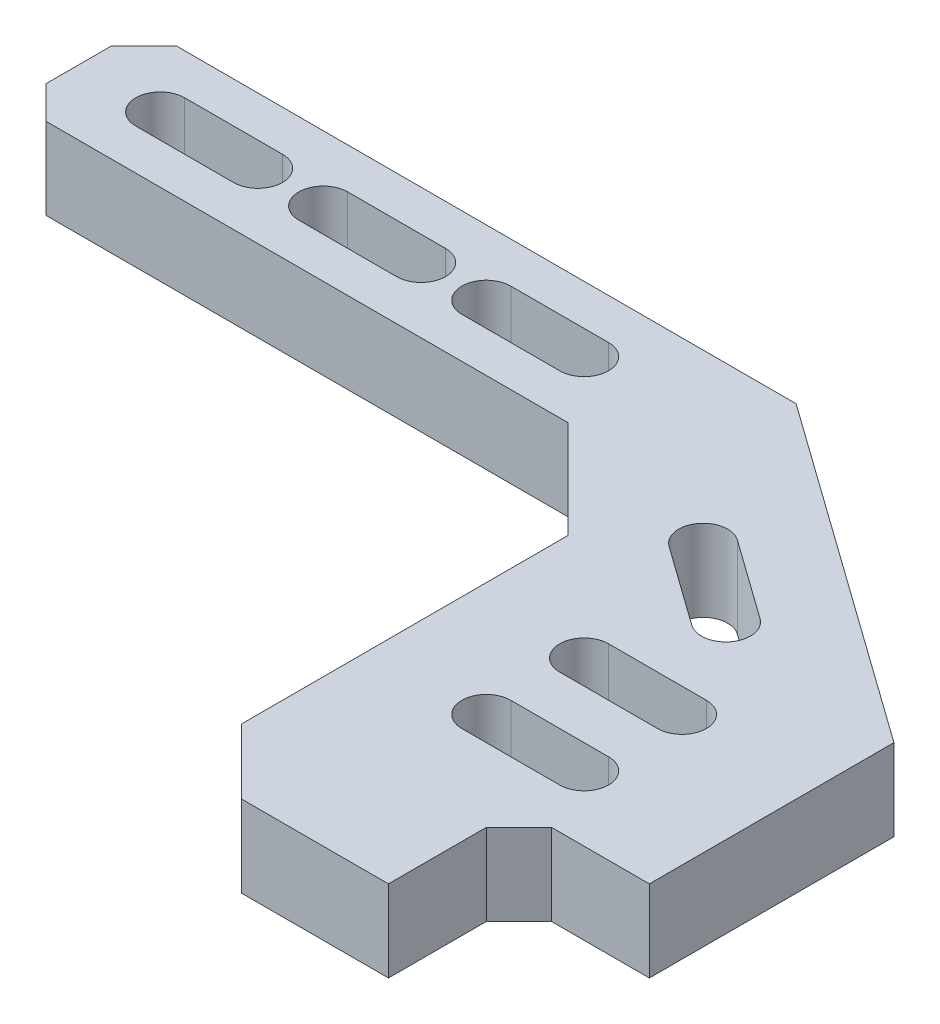
SolidWorks part; units mm, degrees
ref_plane "前视基准面" through (0, 0, 0) normal (0, 0, 1) x (1, 0, 0)
ref_plane "上视基准面" through (0, 0, 0) normal (0, 1, 0) x (1, 0, 0)
ref_plane "右视基准面" through (0, 0, 0) normal (1, 0, 0) x (0, 0, -1)
sketch "草图1" plane through (0, 0, 0) normal (0, 1, 0) x (1, 0, 0)
  line L0 (20, 4) -> (41, -11)
  line L1 (-20, 4) -> (20, 4)
  line L2 (-20, 4) -> (-20, -4)
  line L3 (-20, -4) -> (20, -4)
  line L5 (-20, 4) -> (20, -4) construction
  line L6 (-20, -4) -> (20, 4) construction
  line L8 (20, -4) -> (20, -34)
  line L9 (20, -34) -> (41, -34)
  line L10 (41, -11) -> (41, -34)
  point P0 (0, 0)
  point P5 (0, 0)
  point P8 (41, -6.2971)
  dimension "D1" = 8
  dimension "D2" = 40
  dimension "D3" = 61
  dimension "D4" = 30
  dimension "D5" = 21
  dimension "D6" = 15
extrude "凸台-拉伸1" add sketch "草图1" along normal blind 5
chamfer "倒角1" distance 6 angle 45 1 edges at (20, 2.5, 4)
sketch "草图3" plane through (0, 5, 0) normal (0, 1, 0) x (1, 0, 0)
  line L0 (-15, 0) -> (-9, 0) construction
  line L1 (-15, 1.5) -> (-9, 1.5)
  line L2 (-15, -1.5) -> (-9, -1.5)
  line L3 (-20, 4) -> (-20, -4) construction
  line L4 (-5, -1.5) -> (1, -1.5)
  line L5 (-5, 1.5) -> (1, 1.5)
  line L6 (-5, 0) -> (1, 0) construction
  line L7 (5, -1.5) -> (11, -1.5)
  line L8 (5, 1.5) -> (11, 1.5)
  line L9 (5, 0) -> (11, 0) construction
  line L10 (29.4412, -9.7437) -> (24.5588, -6.2563) construction
  line L11 (28.5693, -10.9643) -> (23.6869, -7.4769)
  line L12 (30.3131, -8.5231) -> (25.4307, -5.0357)
  line L13 (20, 4) -> (-20, 4) construction
  line L14 (20, -10) -> (20, -34) construction
  line L15 (41, -11) -> (20, 4) construction
  line L16 (27, -16) -> (33, -16) construction
  line L17 (27, -14.5) -> (33, -14.5)
  line L18 (27, -17.5) -> (33, -17.5)
  line L20 (33, -34) -> (33, -26)
  line L21 (20, -34) -> (41, -34) construction
  line L22 (33, -26) -> (41, -26)
  line L23 (41, -34) -> (41, -11) construction
  line L24 (33, -34) -> (41, -34)
  line L25 (41, -34) -> (41, -26)
  line L26 (27, -22) -> (33, -22) construction
  line L27 (27, -20.5) -> (33, -20.5)
  line L28 (27, -23.5) -> (33, -23.5)
  arc A0 (-15, 1.5) -> (-15, -1.5) centre (-15, 0) ccw
  arc A1 (-9, -1.5) -> (-9, 1.5) centre (-9, 0) ccw
  arc A2 (-5, 1.5) -> (-5, -1.5) centre (-5, 0) ccw
  arc A3 (1, -1.5) -> (1, 1.5) centre (1, 0) ccw
  arc A4 (5, 1.5) -> (5, -1.5) centre (5, 0) ccw
  arc A5 (11, -1.5) -> (11, 1.5) centre (11, 0) ccw
  arc A6 (28.5693, -10.9643) -> (30.3131, -8.5231) centre (29.4412, -9.7437) ccw
  arc A7 (25.4307, -5.0357) -> (23.6869, -7.4769) centre (24.5588, -6.2563) ccw
  arc A8 (27, -14.5) -> (27, -17.5) centre (27, -16) ccw
  arc A9 (33, -17.5) -> (33, -14.5) centre (33, -16) ccw
  arc A10 (27, -20.5) -> (27, -23.5) centre (27, -22) ccw
  arc A11 (33, -23.5) -> (33, -20.5) centre (33, -22) ccw
  point P2 (-12, 0)
  point P13 (-2, 0)
  point P20 (8, 0)
  point P26 (27, -8)
  point P39 (30, -16)
  point P56 (30, -22)
  dimension "D1" = 6
  dimension "D2" = 5
  dimension "D3" = 3
  dimension "D5" = 4
  dimension "D6" = 12
  dimension "D7" = 7
  dimension "D8" = 10
  dimension "D9" = 10
  dimension "D10" = 8
  dimension "D11" = 13
  dimension "D12" = 2
  dimension "D13" = 4
  dimension "D4" = 3
extrude "切除-拉伸1" cut sketch "草图3" against normal through all both and the other way through all
chamfer "倒角2" distance 2 angle 45 1 edges at (33, 2.5, 26)
chamfer "倒角3" distance 2 angle 45 2 edges at (-20, 2.5, 4) (-20, 2.5, -4)
chamfer "倒角4" distance 4 angle 45 1 edges at (20, 2.5, 34)
